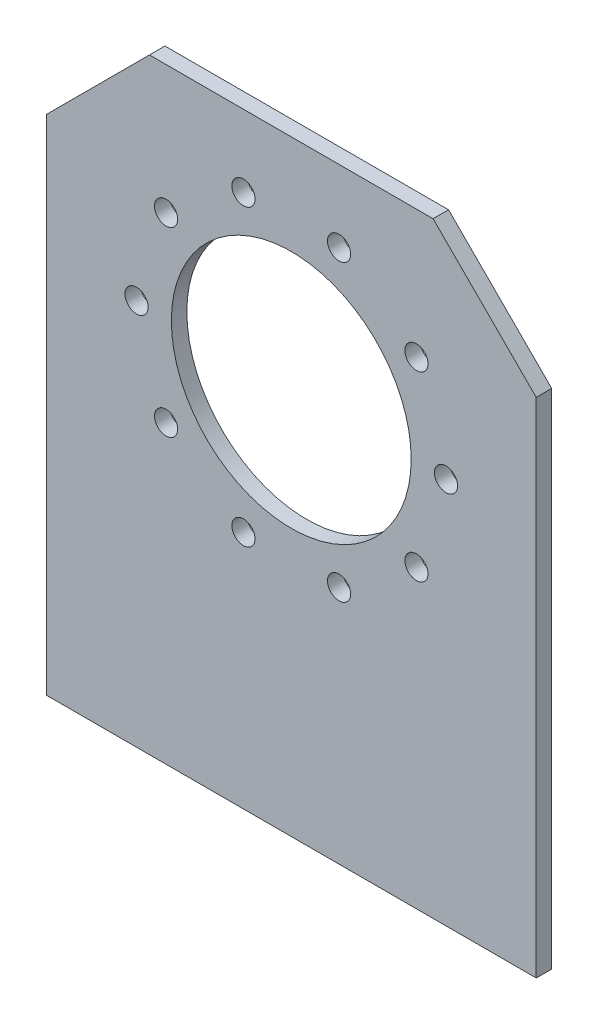
SolidWorks part; units mm, degrees
ref_plane "Front Plane" through (0, 0, 0) normal (0, 0, 1) x (1, 0, 0)
ref_plane "Top Plane" through (0, 0, 0) normal (0, 1, 0) x (1, 0, 0)
ref_plane "Right Plane" through (0, 0, 0) normal (1, 0, 0) x (0, 0, -1)
sketch "Sketch1" plane through (0, 0, 0) normal (0, 0, 1) x (1, 0, 0)
  line L0 (-95, 77.5) -> (-55, 117.5)
  line L1 (-95, -117.5) -> (95, -117.5)
  line L2 (-95, -117.5) -> (-95, 77.5)
  line L3 (-55, 117.5) -> (55, 117.5)
  line L4 (95, -117.5) -> (95, 77.5)
  line L5 (-95, -117.5) -> (95, 117.5) construction
  line L6 (-95, 117.5) -> (95, -117.5) construction
  line L7 (55, 117.5) -> (95, 77.5)
  circle A0 centre (0, 32.5) radius 40.65 construction
  circle A11 centre (0, 32.5) radius 46.5
  circle A31 centre (-60, 32.5) radius 4.5
  circle A32 centre (-48.541, 67.7671) radius 4.5
  circle A33 centre (-18.541, 89.5634) radius 4.5
  circle A34 centre (18.541, 89.5634) radius 4.5
  circle A35 centre (48.541, 67.7671) radius 4.5
  circle A36 centre (60, 32.5) radius 4.5
  circle A37 centre (48.541, -2.7671) radius 4.5
  circle A38 centre (18.541, -24.5634) radius 4.5
  circle A39 centre (-18.541, -24.5634) radius 4.5
  circle A40 centre (-48.541, -2.7671) radius 4.5
  point P0 (0, 0)
  point P14 (-19.103, 6.2069)
  point P18 (-19.103, 6.2069)
  point P19 (-30.9093, 22.4569)
  point P22 (-30.9093, 42.5431)
  point P23 (-30.9093, 22.4569)
  point P25 (-19.103, 58.7931)
  point P27 (-30.9093, 42.5431)
  point P28 (0, 65)
  point P31 (19.103, 58.7931)
  point P32 (-19.103, 58.7931)
  point P34 (30.9093, 42.5431)
  point P36 (0, 65)
  point P37 (30.9093, 22.4569)
  point P40 (19.103, 6.2069)
  point P41 (19.103, 58.7931)
  point P43 (0, 32.5)
  point P45 (30.9093, 42.5431)
  point P48 (30.9093, 22.4569)
  point P51 (19.103, 6.2069)
  point P54 (0, 32.5)
  dimension "D3" = 81.3
  dimension "D5" = 9
  dimension "D11" = 93
  dimension "D1" = 235
  dimension "D2" = 190
  dimension "D4" = 150
  dimension "D6" = 60
  dimension "D7" = 10
  dimension "D10" = 10
extrude "Boss-Extrude1" add sketch "Sketch1" along normal blind 6
